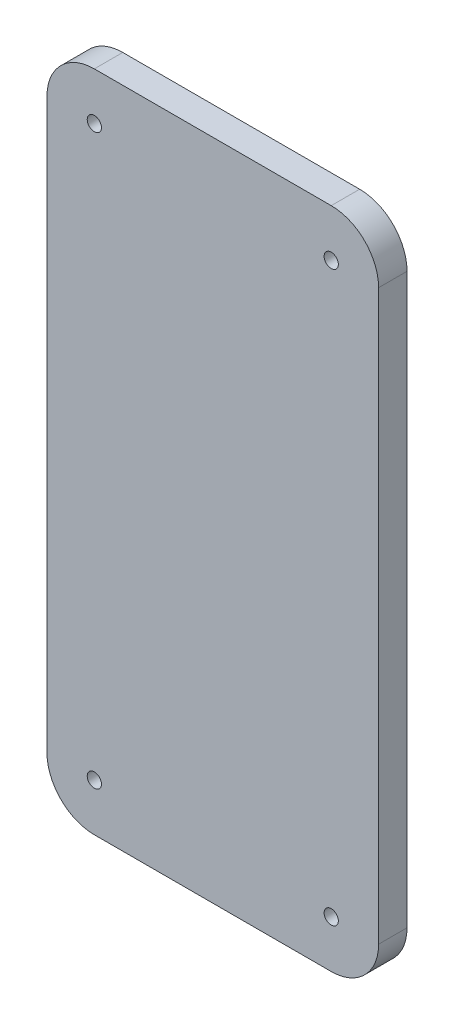
SolidWorks part; units mm, degrees
ref_plane "Front Plane" through (0, 0, 0) normal (0, 0, 1) x (1, 0, 0)
ref_plane "Top Plane" through (0, 0, 0) normal (0, 1, 0) x (1, 0, 0)
ref_plane "Right Plane" through (0, 0, 0) normal (1, 0, 0) x (0, 0, -1)
sketch "Sketch1" plane through (0, 0, 0) normal (0, 0, 1) x (1, 0, 0)
  line L1 (35, -70) -> (-35, -70)
  line L2 (35, -70) -> (35, 70)
  line L3 (35, 70) -> (-35, 70)
  line L4 (-35, -70) -> (-35, 70)
  line L5 (35, -70) -> (-35, 70) construction
  line L6 (35, 70) -> (-35, -70) construction
  point P0 (0, 0)
  dimension "D1" = 70
  dimension "D2" = 140
extrude "Boss-Extrude1" add sketch "Sketch1" along normal blind 6
fillet "Fillet1" radius 10 4 edges at (35, -70, 3) (-35, -70, 3) (-35, 70, 3) (35, 70, 3)
sketch "Sketch2" plane through (0, 0, 6) normal (0, 0, 1) x (1, 0, 0)
  circle A0 centre (-25, 60) radius 1.5
  circle A1 centre (25, 60) radius 1.5
  circle A2 centre (25, -60) radius 1.5
  circle A3 centre (-25, -60) radius 1.5
  dimension "D1" = 3
extrude "Cut-Extrude1" cut sketch "Sketch2" against normal blind 6
